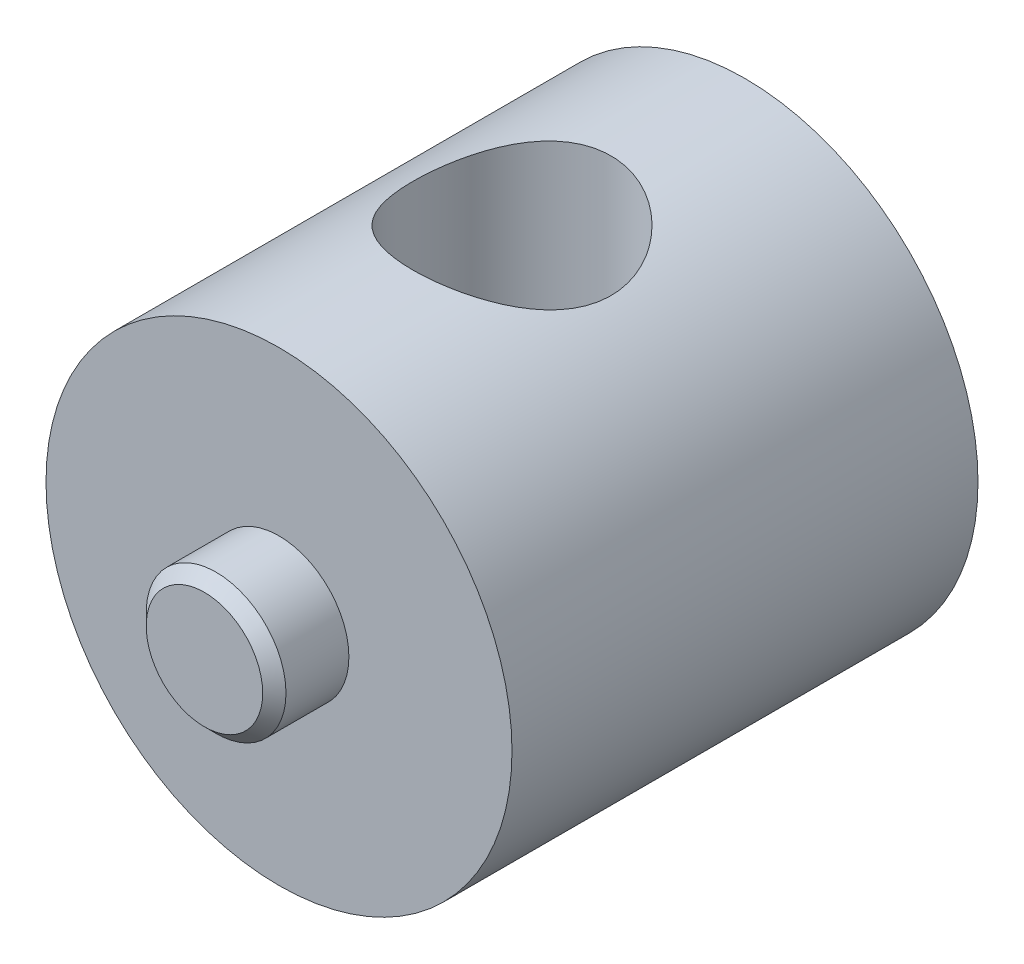
SolidWorks part; units mm, degrees
ref_plane "Piano frontale" through (0, 0, 0) normal (0, 0, 1) x (1, 0, 0)
ref_plane "Piano superiore" through (0, 0, 0) normal (0, 1, 0) x (1, 0, 0)
ref_plane "Piano destro" through (0, 0, 0) normal (1, 0, 0) x (0, 0, -1)
sketch "Schizzo1" plane through (0, 0, 0) normal (0, 0, 1) x (1, 0, 0)
  circle A0 centre (0, 0) radius 10
  dimension "D1" = 20
extrude "Estrusione-Estrusione1" add sketch "Schizzo1" along normal blind 20
ref_plane "Piano1" through (0, 0, 10) normal (0, 0, 1) x (1, 0, 0)
sketch "Schizzo2" plane through (0, 0, 10) normal (0, 0, 1) x (1, 0, 0)
  circle A0 centre (0, 0) radius 3
  dimension "D1" = 6
extrude "Estrusione-Estrusione2" add sketch "Schizzo2" along normal mid plane 26.4
chamfer "Smusso1" distance 0.5 angle 45 2 edges at (3, 0, 23.2) (3, 0, -3.2)
sketch "Schizzo24" plane through (0, 0, 0) normal (0, 1, 0) x (1, 0, 0)
  line L0 (0, 0) -> (0, -20) construction
  line L1 (-3, -20) -> (3, -20) construction
  line L2 (-10, -10) -> (10, -10) construction
  line L3 (-10, 0) -> (-10, -20) construction
  line L4 (10, -20) -> (10, 0) construction
  circle A0 centre (0, -10) radius 4.25
  dimension "D1" = 8.5
hole_wizard "Foro filettato M10-3" positions "Schizzo3D22" profile "Schizzo28" tap size "M10" standard "ISO" end condition through all
sketch3d "Schizzo3D22"
  point P0 (0, 10, 10)
sketch "Schizzo28" plane through (0, 10, 10) normal (1, 0, 0) x (0, 0, 1)
  line L0 (0, 0) -> (0, 20)
  line L1 (0, 20) -> (4.25, 20)
  line L2 (4.25, 20) -> (4.25, 0)
  line L5 (4.25, 0) -> (0, 0)
  line L11 (0, -6.35) -> (0, 107.95) construction
  dimension "Thru Tap Drill Dia." = 8.5
  dimension "Thru Tap Drill Depth" = 20
cosmetic thread "Filettatura del foro3" parameters "D2"=10
